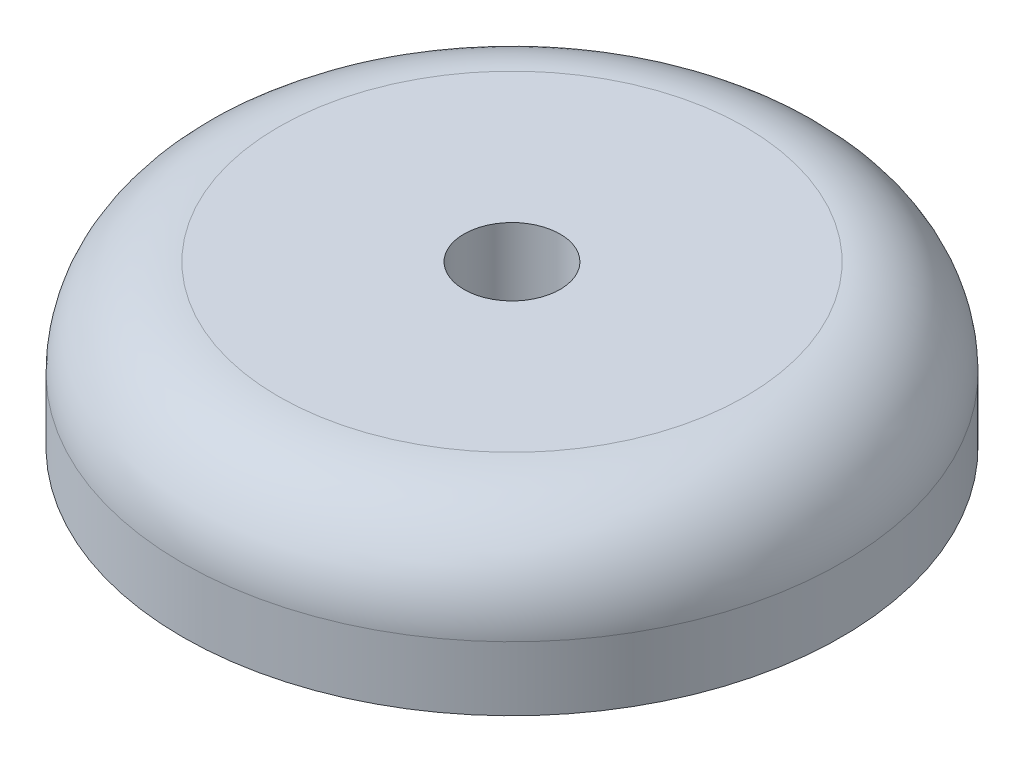
SolidWorks part; units mm, degrees
ref_plane "Front Plane" through (0, 0, 0) normal (0, 0, 1) x (1, 0, 0)
ref_plane "Top Plane" through (0, 0, 0) normal (0, 1, 0) x (1, 0, 0)
ref_plane "Right Plane" through (0, 0, 0) normal (1, 0, 0) x (0, 0, -1)
sketch "Sketch1" plane through (0, 0, 0) normal (0, 1, 0) x (1, 0, 0)
  circle A0 centre (0, 0) radius 12.7 construction
  circle A1 centre (0, 0) radius 1.5
  circle A2 centre (0, 0) radius 10.287
  dimension "D1" = 25.4
  dimension "D2" = 2.413
  dimension "D3" = 3
extrude "Boss-Extrude1" add sketch "Sketch1" along normal blind 5
fillet "Fillet1" radius 3 1 edges at (0, 5, 10.287)
